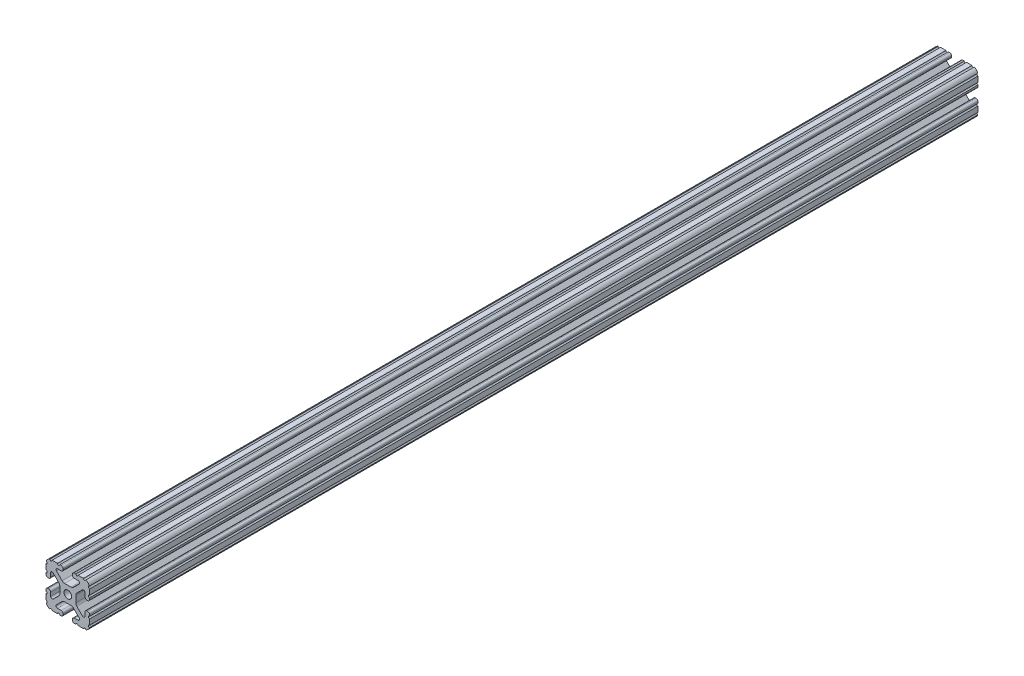
SolidWorks part; units mm, degrees
ref_plane "Front Plane" through (0, 0, 0) normal (0, 0, 1) x (1, 0, 0)
ref_plane "Top Plane" through (0, 0, 0) normal (0, 1, 0) x (1, 0, 0)
ref_plane "Right Plane" through (0, 0, 0) normal (1, 0, 0) x (0, 0, -1)
sketch "Sketch2" plane through (0, 0, 0) normal (0, 0, 1) x (1, 0, 0)
  line L0 (0, 19.05) -> (0, -19.05) construction
  line L1 (-19.05, 0) -> (19.05, 0) construction
  line L2 (4.064, -19.05) -> (19.05, -19.05)
  line L3 (19.05, -19.05) -> (19.05, -4.064)
  line L4 (4.064, -19.05) -> (4.064, -14.986)
  line L5 (4.064, -14.986) -> (12.1123, -14.986)
  line L6 (12.1123, -14.986) -> (4.1113, -6.985)
  line L7 (0, 0) -> (19.05, -19.05) construction
  line L8 (19.05, -4.064) -> (14.986, -4.064)
  line L9 (14.986, -4.064) -> (14.986, -12.1123)
  line L10 (14.986, -12.1123) -> (6.985, -4.1113)
  circle A0 centre (0, 0) radius 3.3274
  arc A1 (8.9963, -14.986) -> (9.909, -12.7826) centre (8.9963, -13.6953) ccw construction
  point P8 (0, -6.985)
  dimension "Center Hole Diameter" = 6.6548
  dimension "Rail Height" = 38.1
  dimension "Rail Width" = 38.1
  dimension "T-Slot Width" = 8.128
  dimension "Slot Inner Width" = 20.574
  dimension "Thickness" = 4.064
  dimension "Slot Depth" = 8.001
  dimension "D1" = 4.064
sketch "Sketch3" plane through (0, 0, 0) normal (1, 0, 0) x (0, 0, -1)
  line L0 (-388.1, -19.05) -> (388.1, -19.05) construction
  line L1 (-362.7, 0) -> (362.7, 0) construction
  dimension "Length" = 776.2
  dimension "D1" = 25.4
sketch "Sketch4" plane through (0, 0, 0) normal (0, 0, 1) x (1, 0, 0)
  line L0 (5.7912, -19.05) -> (14.3002, -19.05)
  line L1 (4.064, -19.05) -> (19.05, -19.05) construction
  line L2 (4.064, -19.05) -> (4.064, -14.986) construction
  line L3 (4.064, -14.986) -> (12.1123, -14.986) construction
  line L4 (4.064, -16.7132) -> (4.064, -17.3228)
  line L5 (5.7912, -14.986) -> (8.9963, -14.986)
  line L6 (0, -6.985) -> (2.833, -6.985)
  line L7 (12.1123, -14.986) -> (4.1113, -6.985) construction
  line L8 (5.0152, -7.8889) -> (9.909, -12.7826)
  line L9 (19.05, -19.05) -> (19.05, -4.064) construction
  line L10 (14.986, -12.1123) -> (6.985, -4.1113) construction
  line L11 (14.986, -4.064) -> (14.986, -12.1123) construction
  line L12 (14.986, -8.9963) -> (14.986, -5.7912)
  line L13 (19.05, -4.064) -> (14.986, -4.064) construction
  line L14 (16.7132, -4.064) -> (17.3228, -4.064)
  line L15 (19.05, -5.7912) -> (19.05, -14.3002)
  line L16 (12.7826, -9.909) -> (7.8889, -5.0152)
  line L17 (6.985, 0) -> (6.985, -2.833)
  line L18 (-19.05, 0) -> (19.05, 0) construction
  line L19 (0, -6.985) -> (0, -3.3274)
  line L20 (0, 19.05) -> (0, -19.05) construction
  line L21 (6.985, 0) -> (3.3274, 0)
  arc A0 (4.064, -17.3228) -> (5.7912, -19.05) centre (5.7912, -17.3228) ccw
  arc A2 (4.064, -16.7132) -> (5.7912, -14.986) centre (5.7912, -16.7132) cw
  arc A3 (8.9963, -14.986) -> (9.909, -12.7826) centre (8.9963, -13.6953) ccw
  arc A4 (2.833, -6.985) -> (5.0152, -7.8889) centre (2.833, -10.0711) cw
  arc A5 (14.3002, -19.05) -> (19.05, -14.3002) centre (14.3002, -14.3002) ccw
  arc A6 (12.7826, -9.909) -> (14.986, -8.9963) centre (13.6953, -8.9963) ccw
  arc A7 (14.986, -5.7912) -> (16.7132, -4.064) centre (16.7132, -5.7912) cw
  arc A8 (17.3228, -4.064) -> (19.05, -5.7912) centre (17.3228, -5.7912) cw
  arc A9 (7.8889, -5.0152) -> (6.985, -2.833) centre (10.0711, -2.833) cw
  circle A10 centre (0, 0) radius 3.3274 construction
  arc A11 (0, -3.3274) -> (3.3274, 0) centre (0, 0) ccw
  dimension "D1" = 4.7498
  dimension "D2" = 3.0861
  dimension "D3" = 1.7272
extrude "Boss-Extrude1" add sketch "Sketch4" along normal mid plane 776.2
sketch "Sketch5" plane through (0, 0, 0) normal (0, 0, 1) x (1, 0, 0)
  line L0 (4.064, -19.05) -> (19.05, -19.05) construction
  line L1 (5.7912, -14.986) -> (8.9963, -14.986) construction
  line L3 (0, 0) -> (19.05, -19.05) construction
  line L4 (8.9963, -14.986) -> (8.9963, -19.05) construction
  line L5 (12.1123, -14.986) -> (4.1113, -6.985) construction
  circle A0 centre (14.7395, -19.05) radius 1.016
  circle A1 centre (7.9803, -19.05) radius 1.016
  circle A2 centre (19.05, -14.7395) radius 1.016
  circle A3 centre (19.05, -7.9803) radius 1.016
  point P10 (7.3938, -14.986)
  point P12 (13.6953, -8.9963)
  dimension "D1" = 2.032
extrude "Cut-Extrude1" cut sketch "Sketch5" against normal through all both and the other way through all
mirror "Mirror1" about plane through (0, 0, 0) normal (1, 0, 0) of bodies 137 134
mirror "Mirror2" about plane through (0, 0, 0) normal (0, 1, 0) of bodies 135
equation "\"D1@Boss-Extrude1\"=\"Length@Sketch3\""
equation "\"D1@Sketch2\"=\"Thickness@Sketch2\""
equation "\"D2@Sketch4\"=\"Slot Inner Width@Sketch2\"*0.15"
equation "\"D1@Sketch4\"=\"D3@Sketch4\"*2.75"
equation "\"D3@Sketch4\"=\"Thickness@Sketch2\"*0.425"
equation "\"D1@Sketch5\"=\"Thickness@Sketch2\"*0.5"
